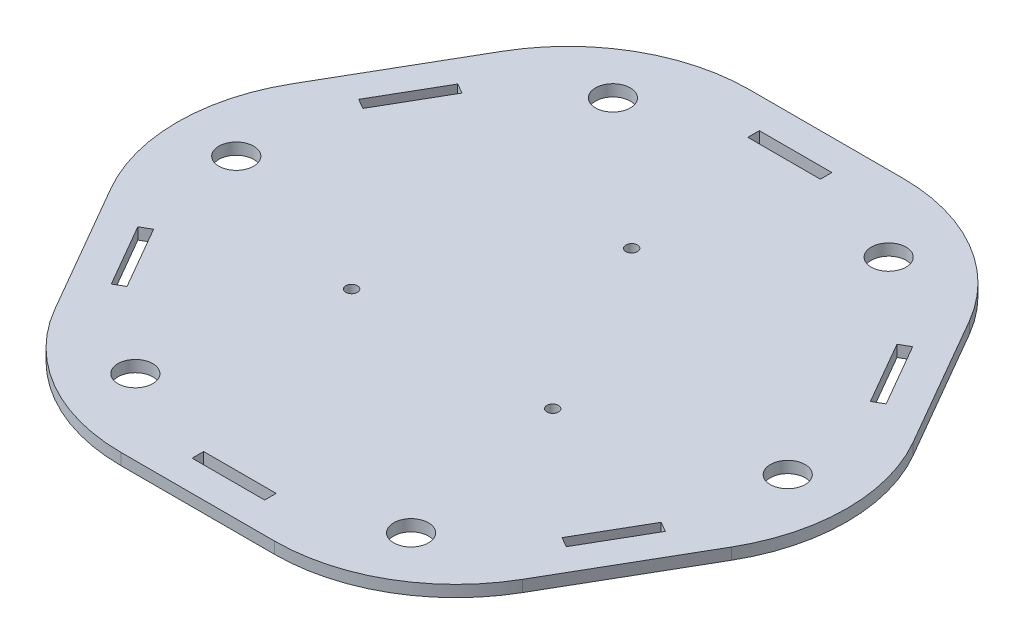
SolidWorks part; units mm, degrees
material "Acrylic (Medium-high impact)"
ref_plane "Front Plane" through (0, 0, 0) normal (0, 0, 1) x (1, 0, 0)
ref_plane "Top Plane" through (0, 0, 0) normal (0, 1, 0) x (1, 0, 0)
ref_plane "Right Plane" through (0, 0, 0) normal (1, 0, 0) x (0, 0, -1)
sketch "Sketch1" plane through (0, 0, 0) normal (0, 1, 0) x (1, 0, 0)
  line L0 (0, 0) -> (200, 0)
  line L1 (171.1325, 50) -> (128.8675, 123.2051)
  line L2 (42.265, 173.2051) -> (-42.265, 173.2051)
  line L3 (-128.8675, 123.2051) -> (-171.1325, 50)
  line L4 (-171.1325, -50) -> (-128.8675, -123.2051)
  line L5 (-42.265, -173.2051) -> (42.265, -173.2051)
  line L6 (128.8675, -123.2051) -> (171.1325, -50)
  line L8 (-20, -150) -> (20, -150)
  line L9 (-20, -150) -> (-20, -156.35)
  line L10 (-20, -156.35) -> (20, -156.35)
  line L11 (20, -150) -> (20, -156.35)
  line L12 (0, -55) -> (0, 55) construction
  line L13 (-55, 0) -> (55, 0) construction
  line L14 (-139.9038, -57.6795) -> (-145.4031, -60.8545)
  line L15 (-139.9038, -57.6795) -> (-119.9038, -92.3205)
  line L16 (-119.9038, -92.3205) -> (-125.4031, -95.4955)
  line L17 (-145.4031, -60.8545) -> (-125.4031, -95.4955)
  line L18 (-119.9038, 92.3205) -> (-125.4031, 95.4955)
  line L19 (-119.9038, 92.3205) -> (-139.9038, 57.6795)
  line L20 (-139.9038, 57.6795) -> (-145.4031, 60.8545)
  line L21 (-125.4031, 95.4955) -> (-145.4031, 60.8545)
  line L22 (20, 150) -> (20, 156.35)
  line L23 (20, 150) -> (-20, 150)
  line L24 (-20, 150) -> (-20, 156.35)
  line L25 (20, 156.35) -> (-20, 156.35)
  line L26 (139.9038, 57.6795) -> (145.4031, 60.8545)
  line L27 (139.9038, 57.6795) -> (119.9038, 92.3205)
  line L28 (119.9038, 92.3205) -> (125.4031, 95.4955)
  line L29 (145.4031, 60.8545) -> (125.4031, 95.4955)
  line L30 (119.9038, -92.3205) -> (125.4031, -95.4955)
  line L31 (119.9038, -92.3205) -> (139.9038, -57.6795)
  line L32 (139.9038, -57.6795) -> (145.4031, -60.8545)
  line L33 (125.4031, -95.4955) -> (145.4031, -60.8545)
  circle A0 centre (0, 0) radius 200 construction
  arc A25 (-42.265, 173.2051) -> (-128.8675, 123.2051) centre (-42.265, 73.2051) ccw
  arc A26 (-171.1325, 50) -> (-171.1325, -50) centre (-84.5299, 0) ccw
  arc A27 (-128.8675, -123.2051) -> (-42.265, -173.2051) centre (-42.265, -73.2051) ccw
  arc A28 (42.265, -173.2051) -> (128.8675, -123.2051) centre (42.265, -73.2051) ccw
  arc A29 (171.1325, -50) -> (171.1325, 50) centre (84.5299, 0) ccw
  arc A30 (128.8675, 123.2051) -> (42.265, 173.2051) centre (42.265, 73.2051) ccw
  point P43 (0, 0)
  point P88 (0, 0)
  point P94 (100, -173.2051)
  dimension "D1" = 400
  dimension "D7" = 6
  dimension "D20" = 100
  dimension "D2" = 200
  dimension "D3" = 40
  dimension "D4" = 20
  dimension "D5" = 6.35
  dimension "D6" = 150
extrude "Boss-Extrude1" add sketch "Sketch1" along normal blind 6.35
sketch "Sketch2" plane through (0, 6.35, 0) normal (0, 1, 0) x (1, 0, 0)
  line L0 (0, -1.1339) -> (85.0289, -1.1339)
  line L1 (0, -55) -> (0, 55) construction
  line L2 (55.7942, -33.3467) -> (0, -1.1339)
  circle A0 centre (55.7942, -33.3467) radius 3.2
  circle A1 centre (-56.7762, -31.6459) radius 3.2
  circle A2 centre (0.982, 64.9926) radius 3.2
  point P14 (0, 0)
  dimension "D3" = 6.4
  dimension "D1" = 65
  dimension "D2" = 30
  dimension "D4" = 3
extrude "Cut-Extrude1" cut sketch "Sketch2" against normal up to surface (6.35 mm away) contours A2 | A0 | A1 up to face at (0, 0, 0)
sketch "Sketch3" plane through (0, 6.35, 0) normal (0, 1, 0) x (1, 0, 0)
  circle A0 centre (76, 131.6359) radius 9.525 construction
  circle A1 centre (76, 131.6359) radius 9.525 construction
  circle A2 centre (76, 131.6359) radius 9.5885
  circle A3 centre (152, 0) radius 9.5885
  circle A4 centre (76, -131.6359) radius 9.5885
  circle A5 centre (-76, -131.6359) radius 9.5885
  circle A6 centre (-152, 0) radius 9.5885
  circle A7 centre (-76, 131.6359) radius 9.5885
  point P17 (0, 0)
  dimension "D1" = 19.177
  dimension "D2" = 6
extrude "Cut-Extrude2" cut sketch "Sketch3" against normal through all
